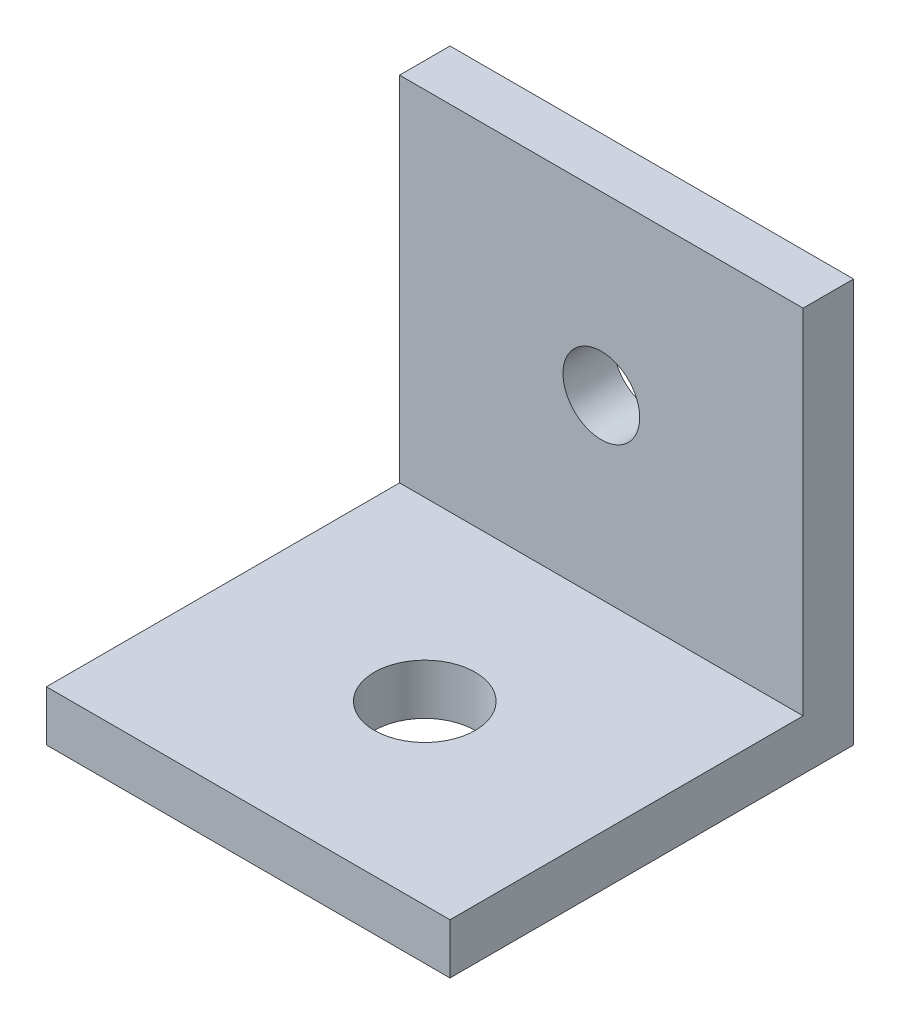
SolidWorks part; units mm, degrees
material "6061-T6 (SS)"
ref_plane "Front Plane" through (0, 0, 0) normal (0, 0, 1) x (1, 0, 0)
ref_plane "Top Plane" through (0, 0, 0) normal (0, 1, 0) x (1, 0, 0)
ref_plane "Right Plane" through (0, 0, 0) normal (1, 0, 0) x (0, 0, -1)
sketch "Sketch1" plane through (0, 0, 0) normal (0, 1, 0) x (1, 0, 0)
  line L1 (-12.7, -12.7) -> (12.7, -12.7)
  line L2 (-12.7, -12.7) -> (-12.7, 12.7)
  line L3 (-12.7, 12.7) -> (12.7, 12.7)
  line L4 (12.7, -12.7) -> (12.7, 12.7)
  line L5 (-12.7, -12.7) -> (12.7, 12.7) construction
  line L6 (-12.7, 12.7) -> (12.7, -12.7) construction
  point P0 (0, 0)
  dimension "D1" = 25.4
  dimension "D2" = 25.4
extrude "Boss-Extrude1" add sketch "Sketch1" along normal blind 3.175
sketch "Sketch6" plane through (0, 3.175, 0) normal (0, 1, 0) x (1, 0, 0)
  line L0 (12.7, -12.7) -> (12.7, 12.7) construction
  line L1 (-12.7, 12.7) -> (12.7, 12.7)
  line L2 (-12.7, 12.7) -> (-12.7, 9.525)
  line L3 (-12.7, 9.525) -> (12.7, 9.525)
  line L4 (12.7, 12.7) -> (12.7, 9.525)
  dimension "D1" = 3.175
extrude "Boss-Extrude2" add sketch "Sketch6" along normal blind 22.225
sketch "Sketch8" plane through (0, 0, -9.525) normal (0, 0, 1) x (1, 0, 0)
  line L0 (-12.7, 3.175) -> (12.7, 25.4) construction
  line L1 (12.7, 3.175) -> (-12.7, 25.4) construction
  circle A0 centre (0, 14.2875) radius 2.413
  dimension "D1" = 4.826
extrude "Cut-Extrude3" cut sketch "Sketch8" against normal blind 3.175
sketch "Sketch9" plane through (0, 3.175, 0) normal (0, 1, 0) x (1, 0, 0)
  line L0 (-12.7, 9.525) -> (12.7, -12.7) construction
  circle A0 centre (0, -1.5875) radius 3.175
  dimension "D1" = 6.35
extrude "Cut-Extrude4" cut sketch "Sketch9" against normal blind 3.175
